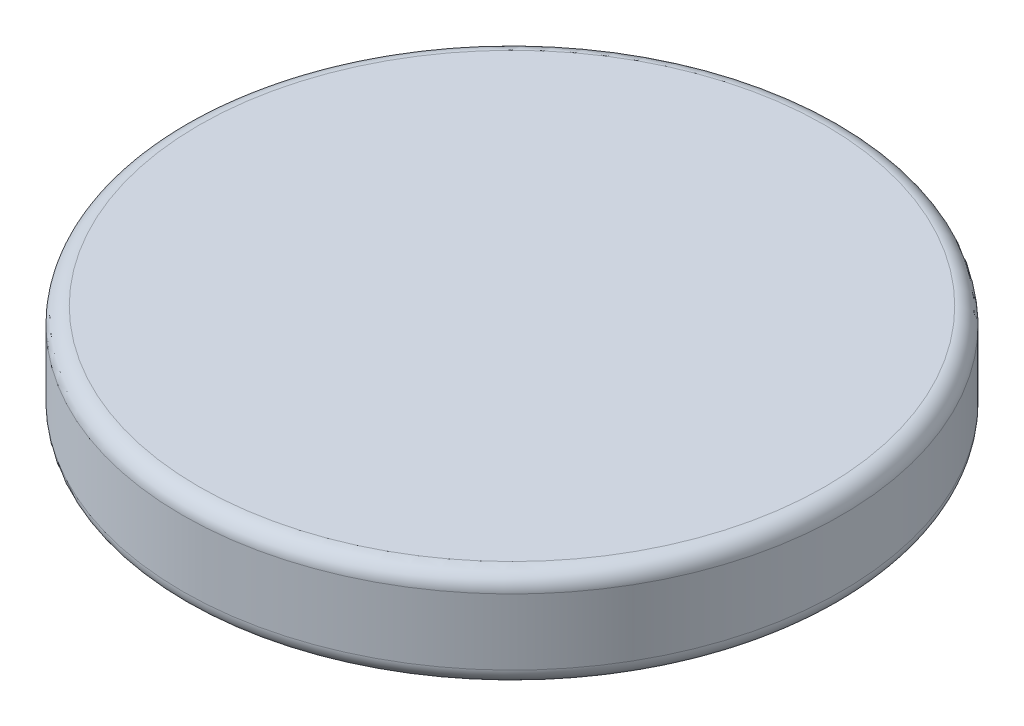
SolidWorks part; units mm, degrees
ref_plane "Front Plane" through (0, 0, 0) normal (0, 0, 1) x (1, 0, 0)
ref_plane "Top Plane" through (0, 0, 0) normal (0, 1, 0) x (1, 0, 0)
ref_plane "Right Plane" through (0, 0, 0) normal (1, 0, 0) x (0, 0, -1)
sketch "Sketch1" plane through (0, 0, 0) normal (0, 1, 0) x (1, 0, 0)
  circle A0 centre (0, 0) radius 10
  dimension "D1" = 20
extrude "Boss-Extrude1" add sketch "Sketch1" along normal mid plane 3
fillet "Fillet1" radius 0.5 2 edges at (0, -1.5, 10) (0, 1.5, 10)
